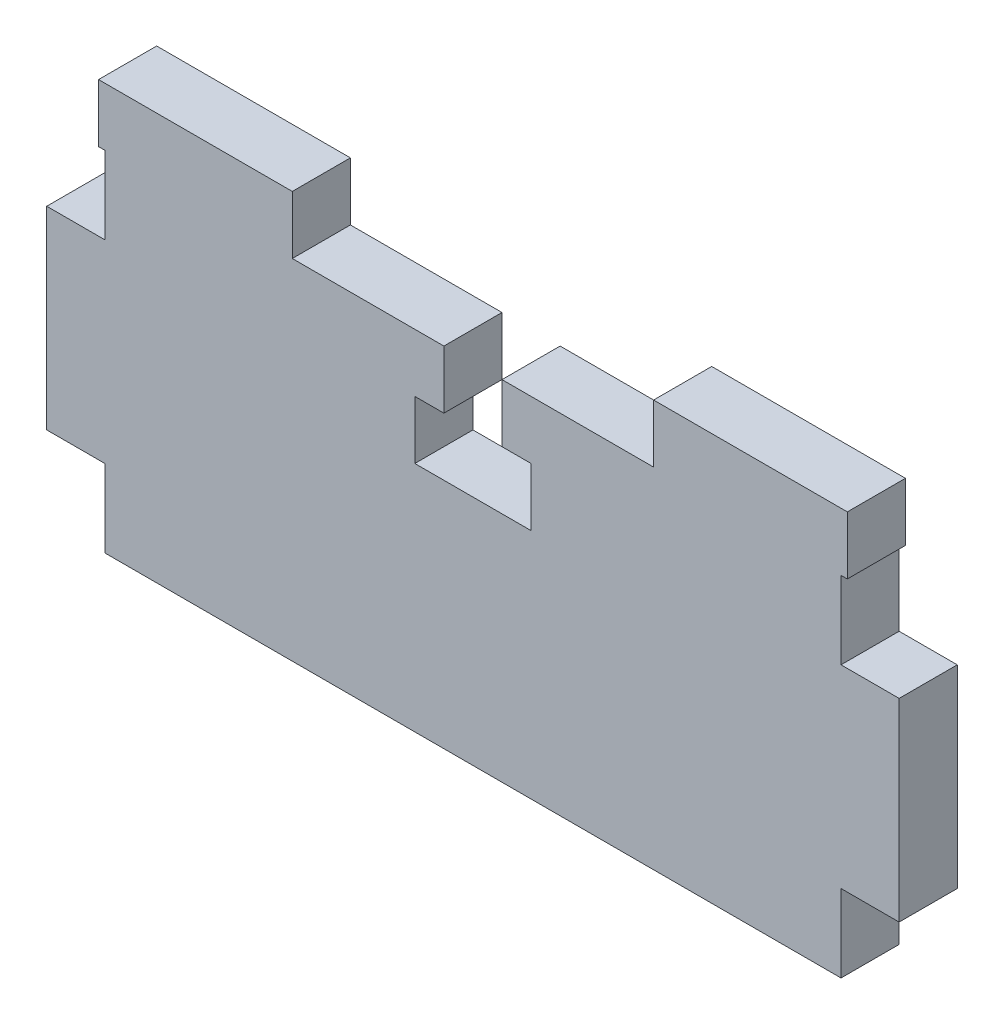
SolidWorks part; units mm, degrees
ref_plane "Alzado" through (0, 0, 0) normal (0, 0, 1) x (1, 0, 0)
ref_plane "Planta" through (0, 0, 0) normal (0, 1, 0) x (1, 0, 0)
ref_plane "Vista lateral" through (0, 0, 0) normal (1, 0, 0) x (0, 0, -1)
sketch "Croquis1" plane through (0, 0, 0) normal (0, 0, 1) x (1, 0, 0)
  line L0 (0, 9) -> (0, -9) construction
  line L1 (19, -9) -> (-19, -9)
  line L2 (19, -9) -> (19, 9)
  line L3 (19, 9) -> (1.5, 9)
  line L4 (-19, -9) -> (-19, 9)
  line L5 (19, -9) -> (-19, 9) construction
  line L6 (19, 9) -> (-19, -9) construction
  line L7 (-1.5, 9) -> (-1.5, 6)
  line L8 (-1.5, 6) -> (-3, 6)
  line L9 (-3, 6) -> (-3, 3)
  line L10 (-3, 3) -> (3, 3)
  line L11 (3, 6) -> (3, 3)
  line L12 (1.5, 9) -> (1.5, 6)
  line L13 (1.5, 6) -> (3, 6)
  line L14 (-1.5, 9) -> (-19, 9)
  line L15 (0, 0) -> (-19, 0) construction
  point P0 (0, 0)
  point P14 (0, 3)
  dimension "D1" = 38
  dimension "D2" = 18
  dimension "D3" = 3
  dimension "D4" = 3
  dimension "D5" = 1.5
  dimension "D6" = 6
extrude "Saliente-Extruir2" add sketch "Croquis1" along normal blind 3
sketch "Croquis2" plane through (19, 0, 0) normal (1, 0, 0) x (0, 0, -1)
  line L0 (-3, 0) -> (0, 0) construction
  line L1 (-3, -9) -> (-3, 9) construction
  line L2 (0, -5) -> (0, 5) construction
  line L3 (0, -9) -> (0, 9) construction
  line L4 (-3.25, 5) -> (0.25, 5) construction
  line L5 (0.25, -5) -> (-3.25, -5) construction
  line L7 (-3, -5) -> (0, -5)
  line L8 (-3, -5) -> (-3, 5)
  line L9 (-3, 5) -> (0, 5)
  line L10 (0, -5) -> (0, 5)
  line L11 (-3, -5) -> (0, 5) construction
  line L12 (-3, 5) -> (0, -5) construction
  point P15 (-1.5, 0)
extrude "Saliente-Extruir3" add sketch "Croquis2" along normal blind 3
sketch "Croquis3" plane through (0, 9, 0) normal (0, 1, 0) x (1, 0, 0)
  line L0 (14.325, -3.25) -> (14.325, 0.25) construction
  line L1 (9.325, -3.25) -> (19.325, -3.25) construction
  line L2 (19.325, 0.25) -> (9.325, 0.25) construction
  line L3 (9.325, 0) -> (19.325, 0) construction
  line L4 (19, 0) -> (1.5, 0) construction
  line L5 (19.325, -3.25) -> (19.325, 0.25) construction
  line L6 (9.325, 0.25) -> (9.325, -3.25) construction
  line L8 (19.325, -3) -> (9.325, -3)
  line L9 (19.325, -3) -> (19.325, 0)
  line L10 (19.325, 0) -> (9.325, 0)
  line L11 (9.325, -3) -> (9.325, 0)
  line L12 (19.325, -3) -> (9.325, 0) construction
  line L13 (19.325, 0) -> (9.325, -3) construction
  point P16 (14.325, -1.5)
extrude "Saliente-Extruir4" add sketch "Croquis3" along normal blind 3
mirror "Simetría1" about plane through (0, 0, 0) normal (1, 0, 0) of "Saliente-Extruir3"
mirror "Simetría2" about plane through (0, 0, 0) normal (1, 0, 0) of "Saliente-Extruir4"
